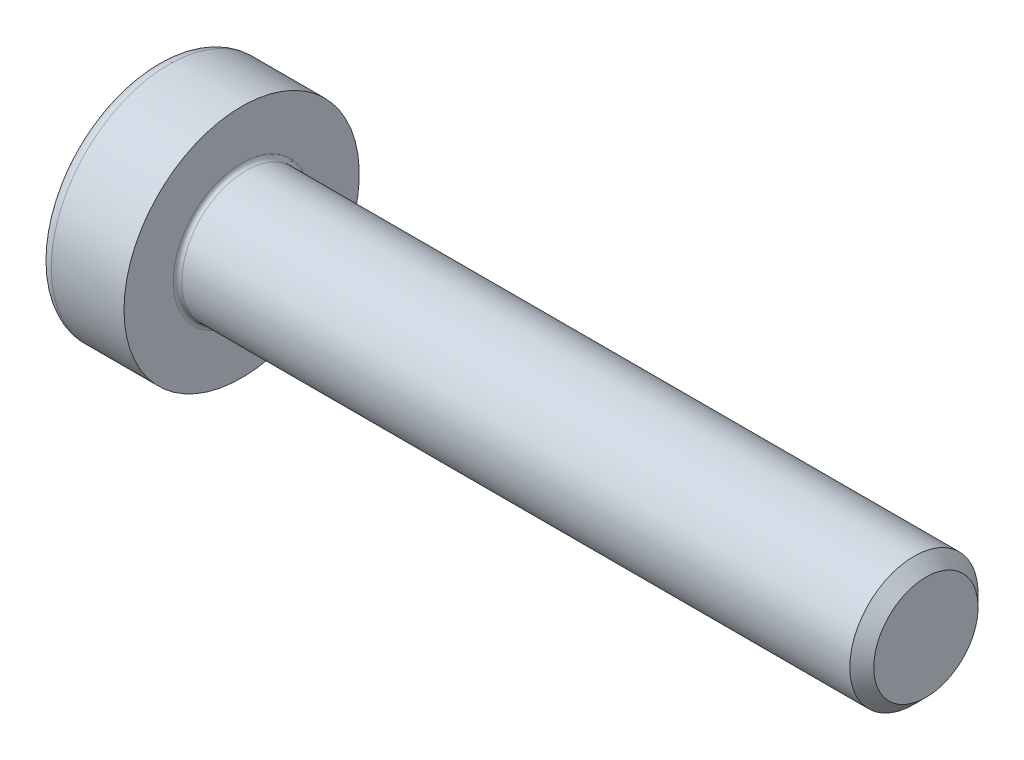
SolidWorks part; units mm, degrees
ref_plane "Plane1" through (0, 0, 0) normal (0, 0, 1) x (1, 0, 0)
ref_plane "Plane2" through (0, 0, 0) normal (0, 1, 0) x (1, 0, 0)
ref_plane "Plane3" through (0, 0, 0) normal (1, 0, 0) x (0, 0, -1)
sketch "BodySke" plane through (0, 0, 0) normal (0, 0, 1) x (1, 0, 0)
  line L0 (0, 0) -> (0, 2.75)
  line L1 (0, 2.75) -> (2, 2.75)
  line L2 (2, 2.75) -> (2, 1.5)
  line L3 (2, 1.5) -> (17.7195, 1.5)
  line L4 (18, 1.2195) -> (18, 0)
  line L5 (18, 0) -> (0, 0)
  line L6 (-31.75, 0) -> (127, 0) construction
  line L8 (18, 1.2195) -> (17.7195, 1.5)
  line L10 (18, -1.2195) -> (17.7195, -1.5) construction
  line L11 (2.5, 4.525) -> (2.5, -1.825) construction
  line L12 (3.5, 4.525) -> (3.5, -1.825) construction
  line L13 (-42, 4.525) -> (-42, -1.825) construction
  dimension "Diameter" = 3
  dimension "Head_ht" = 2
  dimension "Length" = 16
  dimension "Body_ch_ang" = 45
  dimension "Head_dia" = 5.5
  dimension "Minor_dia" = 2.439
  dimension "Advance" = 0.5
  dimension "Thread_nom" = 14.5
  dimension "Thread_length" = 60
revolve "Base-Revolve" add sketch "BodySke"
cosmetic thread "ThreadCosmetic" [suppressed]
fillet "Fillet1" radius 0.1 1 edges at (2, 0, 1.5)
fillet "Fillet2" radius 0.3 1 edges at (0, 0, 2.75)
sketch "Sketch2" plane through (0, 0, 0) normal (0, 0, 1) x (1, 0, 0)
  line L0 (0, 1) -> (1.5, 1)
  line L1 (1.5, 1) -> (2.0774, 0)
  line L2 (-31.75, 0) -> (127, 0) construction
  line L3 (2.0774, 0) -> (0, 0)
  line L4 (0, 0) -> (0, 1)
  line L6 (0, 0) -> (47.625, 0) construction
  dimension "D1" = 1
  dimension "D2" = 60
  dimension "Depth" = 1.5
revolve "Hex-PreBroach" cut sketch "Sketch2" angle 360 about L6
sketch "Sketch3" plane through (0, 0, 0) normal (-1, 0, 0) x (0, 0.5, 0.866)
  line L0 (0.5774, 1) -> (-0.5774, 1)
  line L1 (-0.5774, 1) -> (-1.1547, 0)
  line L2 (0.5774, 1) -> (1.1547, 0)
  line L3 (0.5774, -1) -> (1.1547, 0)
  line L4 (0.5774, -1) -> (-0.5774, -1)
  line L5 (-0.5774, -1) -> (-1.1547, 0)
  dimension "D1" = 1
  dimension "D2" = 1
  dimension "Hex_size" = 2
extrude "Hex" cut sketch "Sketch3" against normal blind 1.5
sketch "ThdSchSke" plane through (0, 0, 0) normal (0, 0, 1) x (1, 0, 0)
  line L0 (3.5, -1.2195) -> (3.3036, -1.5)
  line L1 (3.5, -1.2195) -> (3.6964, -1.5)
  line L2 (3.6964, -1.5) -> (3.6964, -1.875)
  line L3 (-3.175, 0) -> (5.1513, 0) construction
  line L4 (0, 2.45) -> (0, -2.45) construction
  line L5 (3.6964, -1.875) -> (3.3036, -1.875)
  line L6 (3.3036, -1.875) -> (3.3036, -1.5)
  dimension "Thread_minor" = 2.439
  dimension "Diameter" = 3
  dimension "Start" = 3.5
  dimension "SideAngle" = 55
  dimension "VeeAngle" = 70
  dimension "Overcut" = 3.75
revolve "ThreadSchematic" [suppressed] cut sketch "ThdSchSke" angle 360 about L3
pattern_linear "ThdSchPat" [suppressed]
equation "\"D2@Sketch3\" = \"Hex_size@Sketch3\" / 2"
equation "\"D1@Sketch3\" = \"Hex_size@Sketch3\" / 2"
equation "\"D1@Sketch2\" = \"Hex_size@Sketch3\" / 2"
equation "\"Thread_minor@ThreadCosmetic\"  =  \"Minor_dia@BodySke\""
equation "\"Depth@Sketch2\" =  \"Key_eng@Hex\""
equation "\"Thread_length@ThreadCosmetic\" = ((sgn( (\"Length@BodySke\" - \"Advance@BodySke\" * 3.0) - \"Thread_nom@BodySke\" )-1)*( (\"Length@BodySke\" - \"Advance@BodySke\" * 3.0) - \"Thread_nom@BodySke\" ))/-2+ \"Thread_nom@BodySke\""
equation "\"Thread_minor@ThdSchSke\" = \"Minor_dia@BodySke\""
equation "\"Diameter@ThdSchSke\" = \"Diameter@BodySke\""
equation "\"Overcut@ThdSchSke\" = \"Diameter@BodySke\" * 1.25"
equation "\"Start@ThdSchSke\" = \"Head_ht@BodySke\" + \"Length@BodySke\" - \"Thread_length@ThreadCosmetic\"  '---Non-countersunk---"
equation "\"Num_threads@ThdSchPat\" = int( \"Thread_length@ThreadCosmetic\" / \"Advance@BodySke\" + 0.999 )  + 1"
equation "\"Advance@ThdSchPat\" = \"Thread_length@ThreadCosmetic\" /  (\"Num_threads@ThdSchPat\" - 1) 'relax it"
equation "\"Num_threads@ThdSchPat\" = \"Num_threads@ThdSchPat\" - sgn( \"Num_threads@ThdSchPat\" - 1) '---chamfered tips only---"
